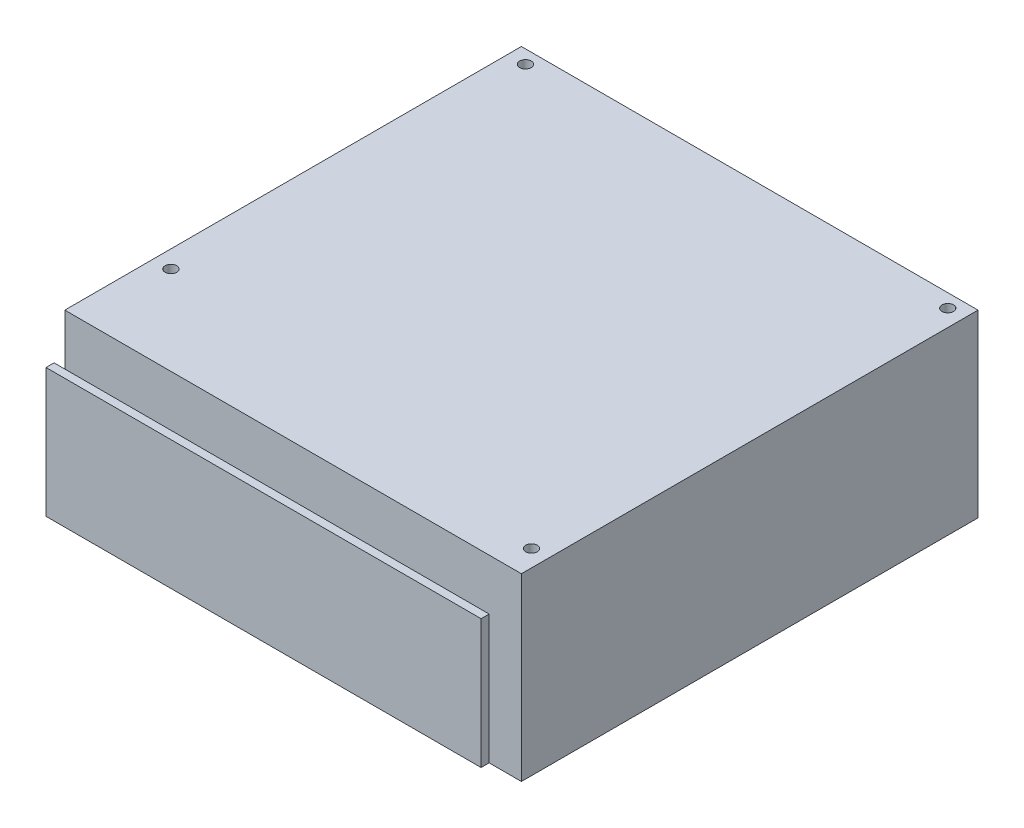
SolidWorks part; units mm, degrees
ref_plane "Front Plane" through (0, 0, 0) normal (0, 0, 1) x (1, 0, 0)
ref_plane "Top Plane" through (0, 0, 0) normal (0, 1, 0) x (1, 0, 0)
ref_plane "Right Plane" through (0, 0, 0) normal (1, 0, 0) x (0, 0, -1)
sketch "Sketch1" plane through (0, 0, 0) normal (0, 1, 0) x (1, 0, 0)
  line L1 (-85, -85) -> (85, -85)
  line L2 (-85, -85) -> (-85, 85)
  line L3 (-85, 85) -> (85, 85)
  line L4 (85, -85) -> (85, 85)
  line L5 (-85, -85) -> (85, 85) construction
  line L6 (-85, 85) -> (85, -85) construction
  point P0 (0, 0)
  dimension "D1" = 170
  dimension "D2" = 170
extrude "Boss-Extrude1" add sketch "Sketch1" along normal blind 67
sketch "Sketch2" plane through (0, 0, 85) normal (0, 0, 1) x (1, 0, 0)
  line L0 (-85, 0) -> (85, 0) construction
  line L1 (73, 0) -> (-89, 0)
  line L2 (73, 0) -> (73, 48)
  line L3 (73, 48) -> (-89, 48)
  line L4 (-89, 0) -> (-89, 48)
  line L5 (85, 67) -> (85, 0) construction
  dimension "D1" = 162
  dimension "D2" = 12
  dimension "D3" = 48
extrude "Boss-Extrude2" add sketch "Sketch2" along normal blind 3
sketch "Sketch3" plane through (0, 67, 0) normal (0, 1, 0) x (1, 0, 0)
  line L0 (85, 85) -> (-85, 85) construction
  line L1 (-78.5, 80) -> (78.75, 80) construction
  line L2 (-78.5, 80) -> (-78.5, -75) construction
  line L3 (-78.5, -75) -> (78.75, -75) construction
  line L4 (78.75, 80) -> (78.75, -75) construction
  line L5 (-85, 85) -> (-85, -85) construction
  line L6 (85, -85) -> (85, 85) construction
  line L7 (-85, -85) -> (85, -85) construction
  point P12 (-78.5, -52)
  dimension "D1" = 5
  dimension "D2" = 6.5
  dimension "D3" = 6.25
  dimension "D4" = 10
  dimension "D5" = 132
hole_wizard "M4 Clearance Hole1" positions "Sketch4" profile "Sketch5" hole size "M4" standard "ANSI Metric" end condition through all
sketch "Sketch4" plane through (0, 67, 0) normal (0, 1, 0) x (1, 0, 0)
  point P0 (-78.5, 80)
  point P3 (-78.5, -52)
  point P6 (78.75, -75)
  point P9 (78.75, 80)
sketch "Sketch5" plane through (-78.5, 67, -80) normal (1, 0, 0) x (0, 0, 1)
  line L0 (0, 0) -> (0, 67)
  line L1 (0, 67) -> (2.15, 67)
  line L2 (2.15, 67) -> (2.15, 0)
  line L5 (2.15, 0) -> (0, 0)
  line L11 (0, -6.35) -> (0, 107.95) construction
  dimension "Thru Hole Dia." = 4.3
  dimension "Thru Hole Depth" = 67
